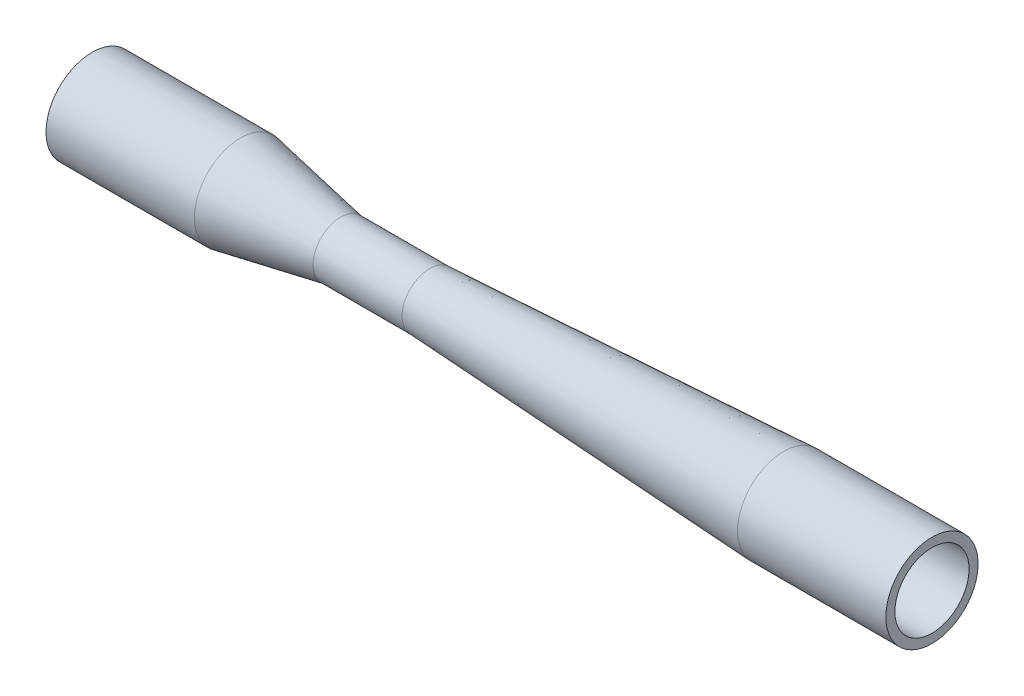
SolidWorks part; units mm, degrees
ref_plane "Front Plane"
ref_plane "Top Plane" through (0, 0, 0) normal (0, 1, 0) x (1, 0, 0)
ref_plane "Right Plane" through (0, 0, 0) normal (1, 0, 0) x (0, 0, -1)
sketch "Sketch1" plane through (0, 0, 0) normal (0, 0, 1) x (1, 0, 0)
  line L0 (0, -68.2655) -> (0, 103.7389) construction
  line L1 (-187.4724, 0) -> (234.4952, 0) construction
  line L2 (0, 12.5) -> (50, 12.5)
  line L3 (50, 12.5) -> (83.722, 6.25)
  line L4 (83.722, 6.25) -> (113.722, 6.25)
  line L5 (113.722, 6.25) -> (232.9791, 12.5)
  line L6 (232.9791, 12.5) -> (282.9791, 12.5)
  line L28 (232.9791, 15.5356) -> (282.9791, 15.5356)
  line L29 (282.9791, 15.5356) -> (282.9791, 12.5)
  line L30 (0, 15.5356) -> (50, 15.5356)
  line L31 (113.722, 9.2856) -> (232.9791, 15.5356)
  line L32 (83.722, 9.2856) -> (113.722, 9.2856)
  line L33 (50, 15.5356) -> (83.722, 9.2856)
  line L34 (0, 12.5) -> (0, 15.5356)
  dimension "D1" = 50
  dimension "D2" = 50
  dimension "D3" = 30
  dimension "D4" = 10.5
  dimension "D5" = 3
  dimension "D6" = 12.5
  dimension "D7" = 12.5
  dimension "D8" = 6.25
  dimension "D9" = 50
  dimension "D10" = 50
  dimension "D11" = 30
revolve "Revolve1" add sketch "Sketch1" angle 360 about L1
sketch "Sketch4" plane through (0, 0, 0) normal (0, 0, 1) x (1, 0, 0)
  point P0 (23.8964, 0)
  point P1 (84.3723, 0)
sketch "Sketch7" plane through (0, 0, 0) normal (-1, 0, 0) x (0, 0, 1)
  circle A0 centre (0, 0) radius 13.9906
